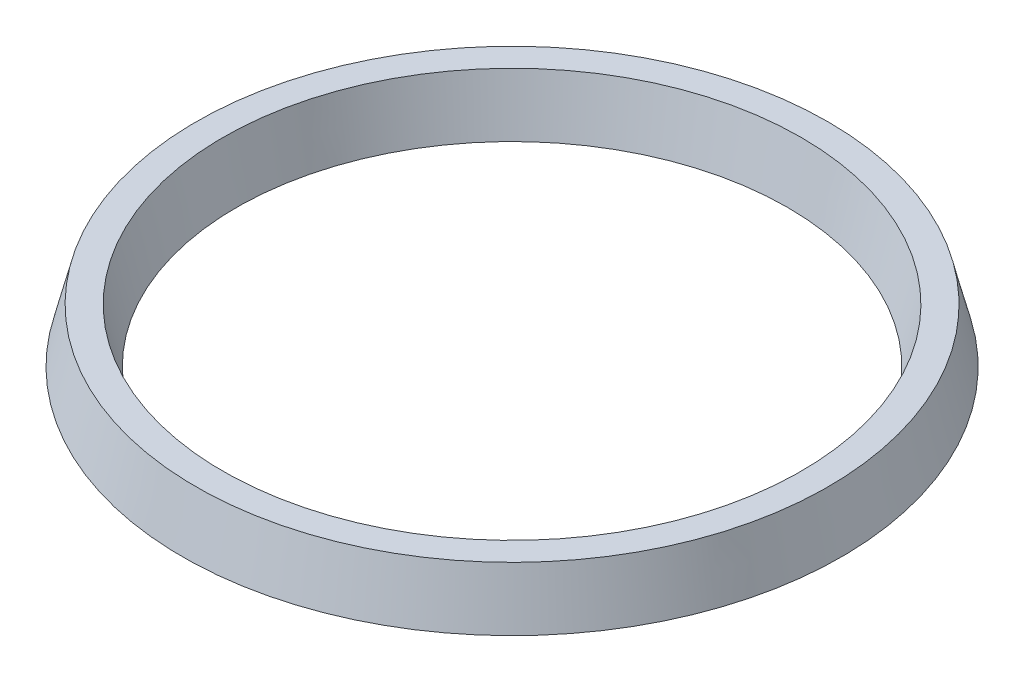
SolidWorks part; units mm, degrees
ref_plane "Front Plane" through (0, 0, 0) normal (0, 0, 1) x (1, 0, 0)
ref_plane "Top Plane" through (0, 0, 0) normal (0, 1, 0) x (1, 0, 0)
ref_plane "Right Plane" through (0, 0, 0) normal (1, 0, 0) x (0, 0, -1)
sketch "Sketch1" plane through (0, 0, 0) normal (0, 0, 1) x (1, 0, 0)
  line L1 (-0.3006, -6) -> (-67.6106, -6) construction
  line L2 (-67.6106, -6) -> (-67.6106, 14.4519) construction
  line L3 (-3.3006, 0) -> (2.6994, 0)
  line L4 (-3.3006, 0) -> (-6.3006, -12)
  line L5 (-6.3006, -12) -> (-3.3006, -12)
  line L6 (-3.3006, -12) -> (-2.4015, -8.4036)
  line L8 (1.8172, -8.4714) -> (2.6994, -12)
  line L9 (2.6994, -12) -> (5.6994, -12)
  line L10 (5.6994, -12) -> (2.6994, 0)
  line L12 (-2.4015, -8.4036) -> (-2.1644, -7.4552)
  line L13 (1.8172, -8.4714) -> (1.5632, -7.4552)
  arc A1 (-2.1644, -7.4552) -> (1.5632, -7.4552) centre (-0.3006, -7.9212) cw
  point P16 (-0.3006, 0)
  dimension "D1" = 6
  dimension "D2" = 12
  dimension "D3" = 3
  dimension "D4" = 12
  dimension "D5" = 6
  dimension "D6" = 6
revolve "Revolve1" add sketch "Sketch1" angle 360 about L2
